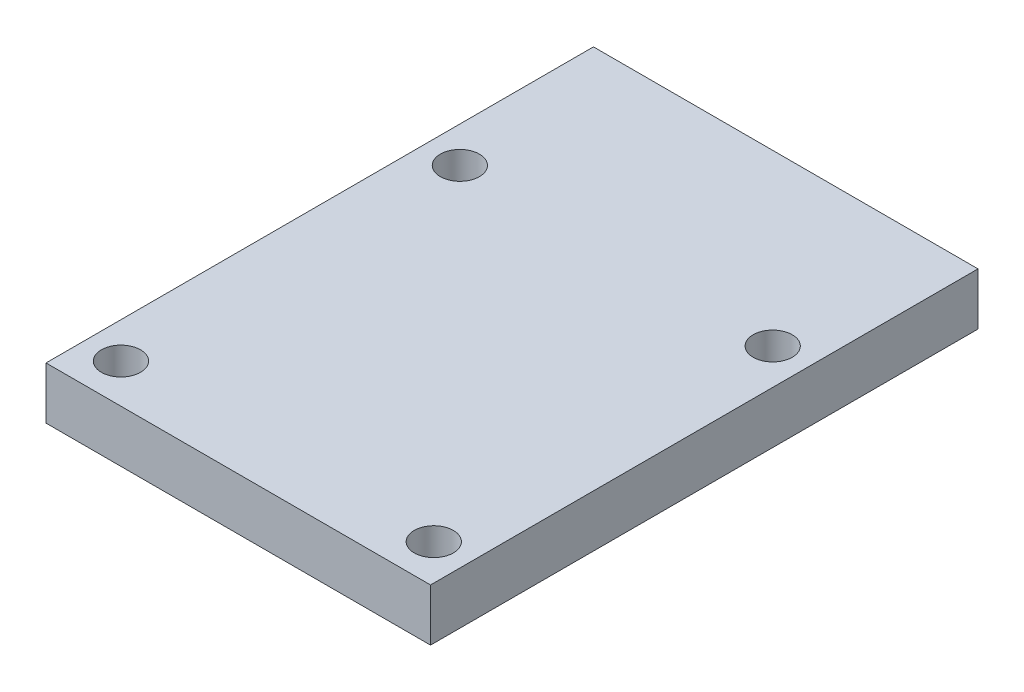
SolidWorks part; units mm, degrees
material "A-玻璃纤维"
ref_plane "前视基准面" through (0, 0, 0) normal (0, 0, 1) x (1, 0, 0)
ref_plane "上视基准面" through (0, 0, 0) normal (0, 1, 0) x (1, 0, 0)
ref_plane "右视基准面" through (0, 0, 0) normal (1, 0, 0) x (0, 0, -1)
other "Configuration Table"
sketch "草图1" plane through (0, 0, 0) normal (0, 1, 0) x (1, 0, 0)
  line L0 (0, 0) -> (0, 16.4137) construction
  line L1 (-14.75, -21) -> (14.75, -21)
  line L2 (-14.75, -21) -> (-14.75, 21)
  line L3 (-14.75, 21) -> (14.75, 21)
  line L4 (14.75, -21) -> (14.75, 21)
  line L5 (-14.75, -21) -> (14.75, 21) construction
  line L6 (-14.75, 21) -> (14.75, -21) construction
  line L7 (0, -5) -> (26.6195, -5) construction
  circle A0 centre (12, 8) radius 1.5
  circle A1 centre (12, -18) radius 1.5
  circle A2 centre (-12, -18) radius 1.5
  circle A3 centre (-12, 8) radius 1.5
  point P0 (0, 0)
  dimension "D3" = 3
  dimension "D4" = 24
  dimension "D5" = 26
  dimension "D1" = 29.5
  dimension "D2" = 42
  dimension "D6" = 5
extrude "凸台-拉伸1" add sketch "草图1" along normal blind 4
